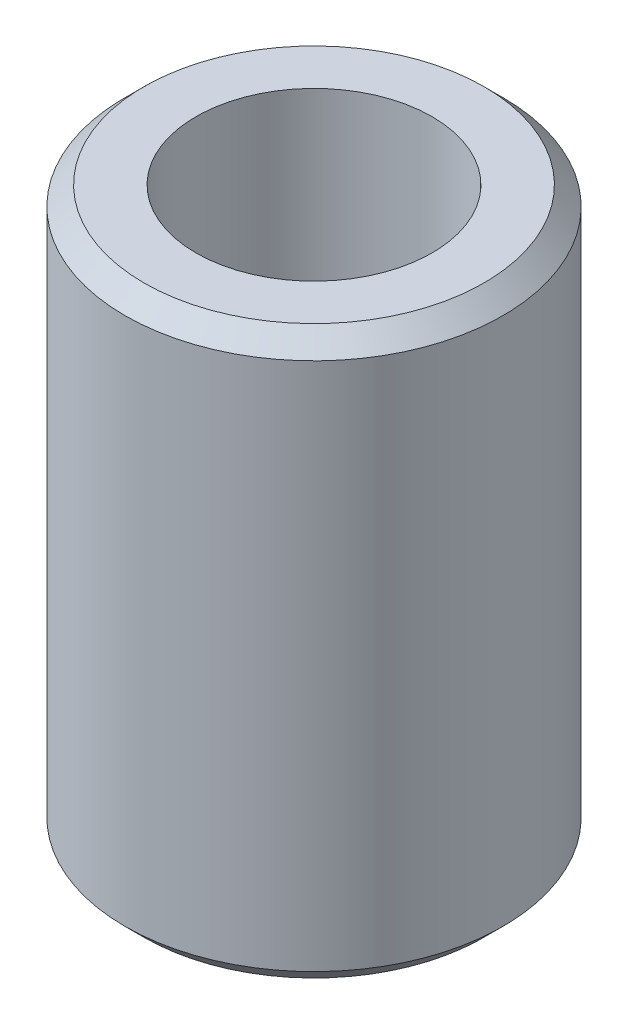
SolidWorks part; units mm, degrees
ref_plane "Front Plane" through (0, 0, 0) normal (0, 0, 1) x (1, 0, 0)
ref_plane "Top Plane" through (0, 0, 0) normal (0, 1, 0) x (1, 0, 0)
ref_plane "Right Plane" through (0, 0, 0) normal (1, 0, 0) x (0, 0, -1)
sketch "Sketch1" plane through (0, 0, 0) normal (0, 1, 0) x (1, 0, 0)
  circle A0 centre (0, 0) radius 20
  circle A1 centre (0, 0) radius 12.5
  dimension "D1" = 40
  dimension "D2" = 25
extrude "Boss-Extrude1" add sketch "Sketch1" along normal mid plane 60
chamfer "Chamfer1" distance 2 angle 45 2 edges at (0, -30, 20) (0, 30, 20)
